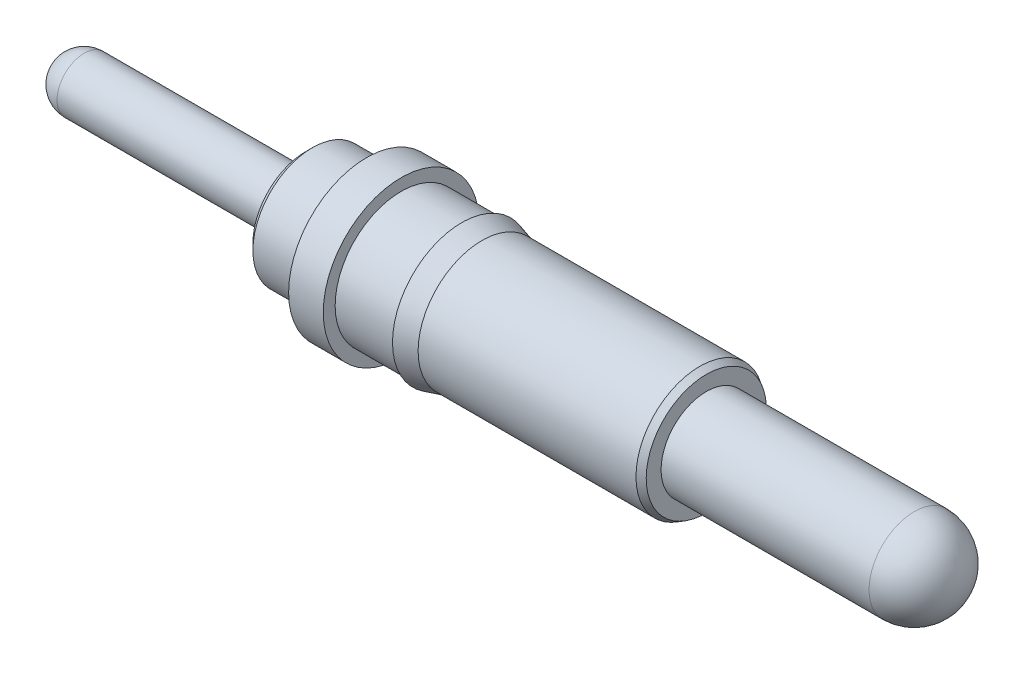
SolidWorks part; units mm, degrees
material "Brass Alloy 385"
ref_plane "Front Plane" through (0, 0, 0) normal (0, 0, 1) x (1, 0, 0)
ref_plane "Top Plane" through (0, 0, 0) normal (0, 1, 0) x (1, 0, 0)
ref_plane "Right Plane" through (0, 0, 0) normal (1, 0, 0) x (0, 0, -1)
sketch "Sketch1" plane through (0, 0, 0) normal (0, 0, 1) x (1, 0, 0)
  line L0 (0, 0) -> (13.8006, 0) construction
  line L1 (0, 0) -> (10.5918, 0)
  line L4 (0.3175, 0.3175) -> (2.921, 0.3175)
  line L5 (2.921, 0.3175) -> (2.921, 0.6223)
  line L6 (2.921, 0.6223) -> (2.9972, 0.6985)
  line L7 (2.9972, 0.6985) -> (3.6322, 0.6985)
  line L8 (3.6322, 0.6985) -> (3.6322, 0.9144)
  line L9 (3.6322, 0.9144) -> (4.0386, 0.9144)
  line L10 (4.0386, 0.9144) -> (4.0386, 0.7747)
  line L11 (4.0386, 0.7747) -> (4.7498, 0.7747)
  line L12 (4.7498, 0.7747) -> (4.7498, 0.8128)
  line L13 (4.7498, 0.8128) -> (4.9868, 0.7493)
  line L14 (4.9868, 0.7493) -> (7.5438, 0.7493)
  line L15 (7.5438, 0.7493) -> (7.62, 0.7053)
  line L16 (7.62, 0.7053) -> (7.62, 0.5309)
  line L17 (7.62, 0.5309) -> (10.0609, 0.5309)
  arc A0 (10.5918, 0) -> (10.0609, 0.5309) centre (10.0609, 0) ccw
  arc A2 (0.3175, 0.3175) -> (0, 0) centre (0.3175, 0) ccw
  dimension "D1" = 0.3175
  dimension "D14" = 0.5309
  dimension "D2" = 0.635
  dimension "D3" = 1.397
  dimension "D4" = 1.8288
  dimension "D5" = 1.4986
  dimension "D6" = 1.0617
  dimension "D7" = 1.6256
  dimension "D8" = 1.5494
  dimension "D9" = 15
  dimension "D10" = 30
  dimension "D11" = 0.4064
  dimension "D12" = 0.7112
  dimension "D13" = 0.7112
  dimension "B" = 4.699
  dimension "D15" = 2.921
  dimension "A" = 6.9596
  dimension "D17" = 0.0762
  dimension "D20" = 45
  dimension "D21" = 0.0762
revolve "Revolve1" add sketch "Sketch1" angle 360 about L0
